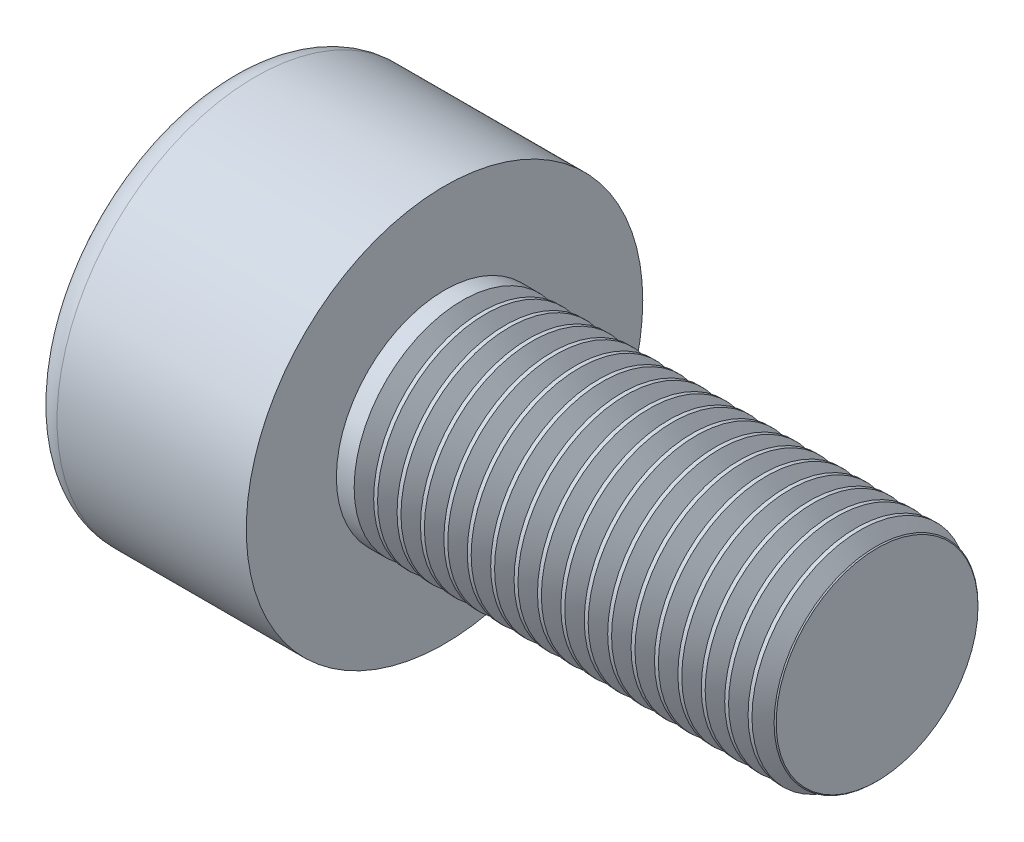
SolidWorks part; units mm, degrees
ref_plane "Front" through (0, 0, 0) normal (0, 0, 1) x (1, 0, 0)
ref_plane "Top" through (0, 0, 0) normal (0, 1, 0) x (1, 0, 0)
ref_plane "Right" through (0, 0, 0) normal (1, 0, 0) x (0, 0, -1)
sketch "Sketch1" plane through (0, 0, 0) normal (1, 0, 0) x (0, 0, -1)
  circle A0 centre (0, 0) radius 2.75
  dimension "dk" = 5.5
extrude "BaseHead" add sketch "Sketch1" along normal blind 3
sketch "Sketch2" plane through (3, 0, 0) normal (1, 0, 0) x (0, 0, -1)
  circle A0 centre (0, 0) radius 1.5
  dimension "d" = 3
extrude "BaseBody" add sketch "Sketch2" along normal blind 6
cosmetic thread "ThreadCosmetic1" [suppressed] parameters "b"=6, "D2"=2.459
sketch "Sketch3" plane through (0, 0, 0) normal (1, 0, 0) x (0, 0, -1)
  line L1 (1.4434, 0) -> (0.7217, 1.25)
  line L2 (0.7217, 1.25) -> (-0.7217, 1.25)
  line L3 (-0.7217, 1.25) -> (-1.4434, 0)
  line L4 (-1.4434, 0) -> (-0.7217, -1.25)
  line L5 (-0.7217, -1.25) -> (0.7217, -1.25)
  line L6 (0.7217, -1.25) -> (1.4434, 0)
  circle A0 centre (0, 0) radius 1.25 construction
  dimension "s" = 2.5
  dimension "e" = 2.8868
extrude "HexagonSocket" cut sketch "Sketch3" along normal blind 1.3
sketch "Sketch4" plane through (-4.1961, 0.75, 0) normal (0, 0, 1) x (-1, 0, 0)
  line L0 (-5.4961, 2) -> (-6.2178, 0.75)
  line L2 (-6.2178, 0.75) -> (-5.4961, 0.75)
  line L3 (-5.4961, 0.75) -> (-5.4961, 2)
  line L4 (-5.0351, 0.75) -> (0.839, 0.75) construction
  line L5 (-13.1961, 0.75) -> (-7.1961, 0.75) construction
  line L6 (-7.1961, 0.75) -> (-4.1961, 0.75) construction
  dimension "m" = 60
revolve "Cut-Revolve1" cut sketch "Sketch4" angle 360 about L4
fillet "HeadFillet" [suppressed] radius 0.1
fillet "TopFillet" radius 0.375 1 edges at (0, 0, -2.75)
chamfer "Chamfer1" distance 0.1 angle 45 1 edges at (9, 0, -1.5)
sketch "Sketch5" plane through (0, 0, 0) normal (0, 0, 1) x (1, 0, 0)
  line L0 (8.9, 1.2657) -> (9.0353, 1.5)
  line L1 (9.0353, 1.5) -> (9.0353, 1.7705)
  line L2 (9.0353, 1.7705) -> (8.7648, 1.7705)
  line L3 (8.7648, 1.7705) -> (8.7648, 1.5)
  line L4 (8.7648, 1.5) -> (8.9, 1.2657)
  line L5 (0, 0) -> (7.8886, 0) construction
  line L6 (8.9, -1.5) -> (8.9, 1.5) construction
  dimension "D1" = 3
  dimension "D2" = 0.2705
revolve "Cut-Revolve10" cut sketch "Sketch5" angle 360 about L5
pattern_linear "LPattern10" count 18 spacing 0.3246 along (-1, 0, 0) of "Cut-Revolve10"
equation "\"r1@TopFillet\" = \"d@Sketch2\" / 8"
equation "\"D1@Chamfer1\" = \"r@HeadFillet\""
equation "\"D1@Sketch5\" = \"d@Sketch2\""
equation "\"D2@Sketch5\" =  ( \"d@Sketch2\" - \"D2@ThreadCosmetic1\" )  / 2"
equation "\"D3@LPattern10\" = \"D2@Sketch5\" * 1.2"
equation "\"D1@LPattern10\" = \"b@ThreadCosmetic1\" / \"D3@LPattern10\""
